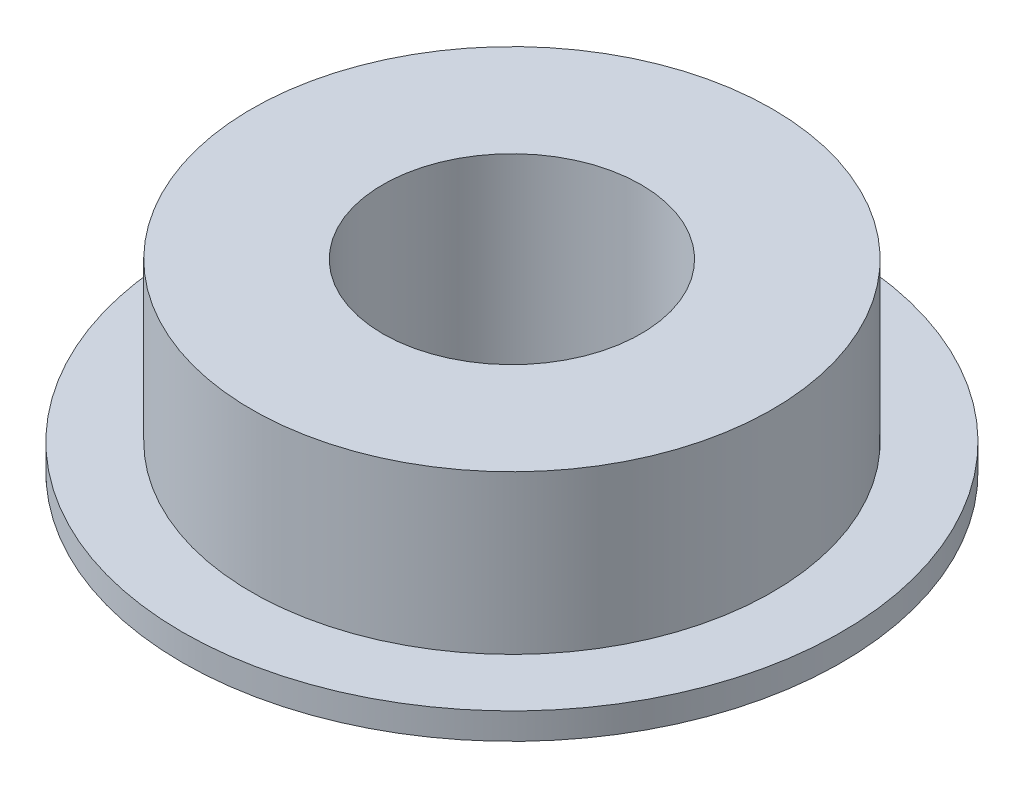
SolidWorks part; units mm, degrees
ref_plane "Front Plane" through (0, 0, 0) normal (0, 0, 1) x (1, 0, 0)
ref_plane "Top Plane" through (0, 0, 0) normal (0, 1, 0) x (1, 0, 0)
ref_plane "Right Plane" through (0, 0, 0) normal (1, 0, 0) x (0, 0, -1)
sketch "Sketch1" plane through (0, 0, 0) normal (0, 1, 0) x (1, 0, 0)
  circle A0 centre (0, 0) radius 6.35
  circle A2 centre (0, 0) radius 2.4892
  dimension "D1" = 4.9784
  dimension "D2" = 12.7
extrude "Boss-Extrude1" add sketch "Sketch1" along normal blind 0.508
sketch "Sketch2" plane through (0, 0.508, 0) normal (0, 1, 0) x (1, 0, 0)
  circle A0 centre (0, 0) radius 2.4892
  circle A1 centre (0, 0) radius 5.0165
  circle A2 centre (0, 0) radius 2.4892 construction
  dimension "D1" = 10.033
extrude "Boss-Extrude2" add sketch "Sketch2" along normal blind 3.048
